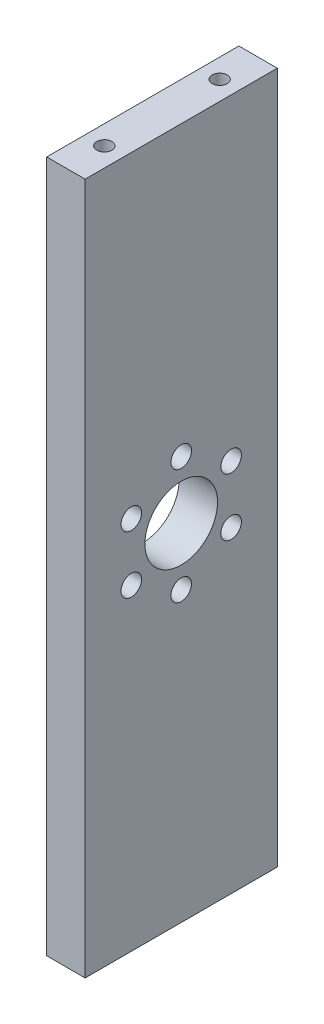
SolidWorks part; units mm, degrees
ref_plane "Front Plane" through (0, 0, 0) normal (0, 0, 1) x (1, 0, 0)
ref_plane "Top Plane" through (0, 0, 0) normal (0, 1, 0) x (1, 0, 0)
ref_plane "Right Plane" through (0, 0, 0) normal (1, 0, 0) x (0, 0, -1)
sketch "Sketch1" plane through (0, 0, 0) normal (1, 0, 0) x (0, 0, -1)
  line L1 (-15.875, -57.15) -> (15.875, -57.15)
  line L2 (-15.875, -57.15) -> (-15.875, 57.15)
  line L3 (-15.875, 57.15) -> (15.875, 57.15)
  line L4 (15.875, -57.15) -> (15.875, 57.15)
  line L5 (-15.875, -57.15) -> (15.875, 57.15) construction
  line L6 (-15.875, 57.15) -> (15.875, -57.15) construction
  point P0 (0, 0)
  dimension "D1" = 31.75
  dimension "D2" = 114.3
extrude "Boss-Extrude1" add sketch "Sketch1" along normal mid plane 6.35
sketch "Sketch2" plane through (0, 57.15, 0) normal (0, 1, 0) x (1, 0, 0)
  line L0 (0, 9.525) -> (0, -9.525) construction
  line L1 (-3.175, 15.875) -> (-3.175, -15.875) construction
  line L2 (3.175, 15.875) -> (-3.175, 15.875) construction
  point P2 (0, 0)
  point P5 (-3.175, 0)
  point P8 (0, 15.875)
  point P10 (0, 9.525)
  point P11 (0, -9.525)
  dimension "D1" = 19.05
hole_wizard "M3x0.5 Tapped Hole1" positions "Sketch3" profile "Sketch5" tap size "M3x0.5" standard "ANSI Metric"
sketch "Sketch3" plane through (0, 57.15, 0) normal (0, 1, 0) x (1, 0, 0)
  point P0 (0, 9.525)
  point P3 (0, -9.525)
sketch "Sketch5" plane through (0, 57.15, -9.525) normal (1, 0, 0) x (0, 0, 1)
  line L0 (0, 0) -> (0, 13.4511)
  line L1 (0, 13.4511) -> (1.25, 12.7)
  line L2 (1.25, 12.7) -> (1.25, 0)
  line L5 (1.25, 0) -> (0, 0)
  line L10 (0, 13.4511) -> (-1.25, 12.7) construction
  line L11 (0, -6.35) -> (0, 107.95) construction
  dimension "Tap Drill Dia." = 2.5
  dimension "Tap Drill Depth" = 12.7
  dimension "Drill Angle" = 118
cosmetic thread "Hole Thread1" parameters "D1"=6.096, "D2"=3
cosmetic thread "Hole Thread2" parameters "D1"=6.096, "D2"=3
mirror "Mirror1" about plane through (0, 0, 0) normal (0, 1, 0) of "M3x0.5 Tapped Hole1"
cosmetic thread "Hole Thread3" parameters "D1"=6.096, "D2"=3
cosmetic thread "Hole Thread4" parameters "D1"=6.096, "D2"=3
sketch "Sketch6" plane through (-3.175, 0, 0) normal (-1, 0, 0) x (0, 0, 1)
  point P0 (0, 0)
hole_wizard "Ø12.0mm Dowel Hole1" positions "Sketch7" profile "Sketch8" hole size "Ø12.0" standard "ANSI Metric" end condition through all
sketch "Sketch7" plane through (-3.175, 0, 0) normal (-1, 0, 0) x (0, 0, 1)
  point P0 (0, 0)
sketch "Sketch8" plane through (-3.175, 0, 0) normal (0, 1, 0) x (0, 0, 1)
  line L0 (0, 0) -> (0, 6.35)
  line L1 (0, 6.35) -> (6, 6.35)
  line L2 (6, 6.35) -> (6, 0)
  line L5 (6, 0) -> (0, 0)
  line L11 (0, -6.35) -> (0, 107.95) construction
  dimension "Thru Hole Dia." = 12
  dimension "Thru Hole Depth" = 6.35
sketch "Sketch9" plane through (-3.175, 0, 0) normal (-1, 0, 0) x (0, 0, 1)
  point P0 (0, 9.525)
  point P1 (8.2489, 4.7625)
  point P3 (8.2489, -4.7625)
  point P5 (0, -9.525)
  point P7 (-8.2489, -4.7625)
  point P9 (-8.2489, 4.7625)
hole_wizard "CBORE for M3 SHCS1" positions "Sketch10" profile "Sketch11" counterbore size "M3" standard "ANSI Metric"
sketch "Sketch10" plane through (-3.175, 0, 0) normal (-1, 0, 0) x (0, 0, 1)
  point P0 (8.2489, -4.7625)
  point P3 (8.2489, 4.7625)
  point P6 (0, 9.525)
  point P9 (-8.2489, 4.7625)
  point P12 (-8.2489, -4.7625)
  point P15 (0, -9.525)
sketch "Sketch11" plane through (-3.175, -4.7625, 8.2489) normal (0, 1, 0) x (0, 0, 1)
  line L0 (0, 0) -> (0, 12.7)
  line L1 (0, 12.7) -> (1.7, 11.6785)
  line L2 (1.7, 11.6785) -> (1.7, 2)
  line L3 (1.7, 2) -> (2.25, 2)
  line L4 (2.25, 2) -> (2.25, 0)
  line L5 (2.25, 0) -> (0, 0)
  line L10 (0, 12.7) -> (-1.7, 11.6785) construction
  line L11 (0, -6.35) -> (0, 107.95) construction
  dimension "Hole Dia." = 3.4
  dimension "Hole Depth" = 12.7
  dimension "C'Bore Dia." = 4.5
  dimension "C'Bore Depth" = 2
  dimension "Drill Angle" = 118
